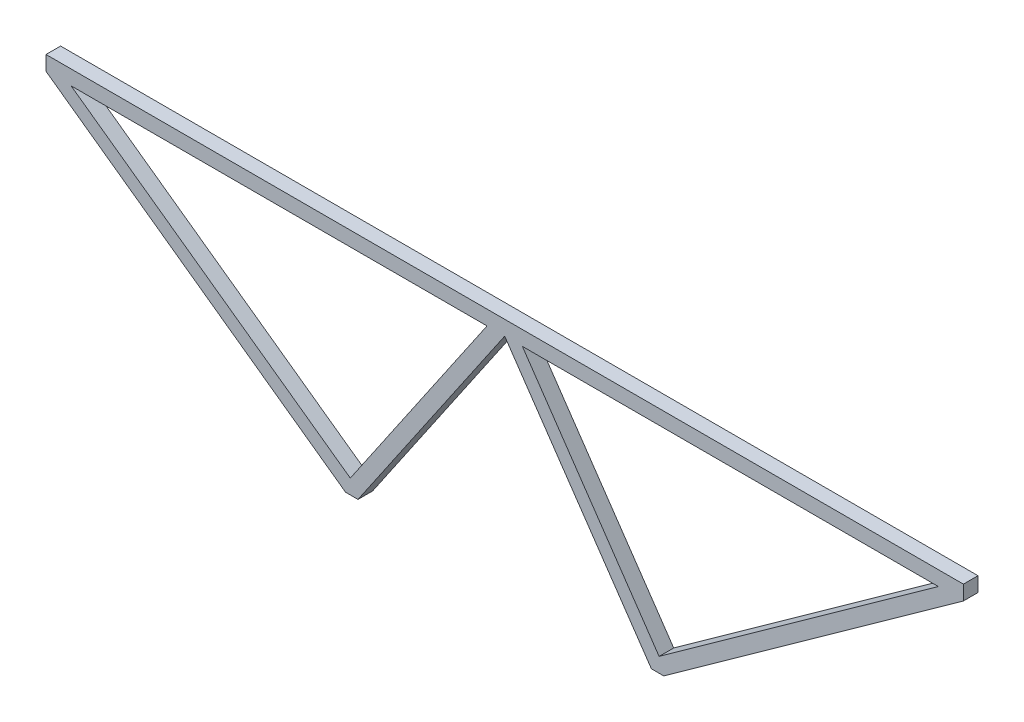
SolidWorks part; units mm, degrees
ref_plane "Front Plane" through (0, 0, 0) normal (0, 0, 1) x (1, 0, 0)
ref_plane "Top Plane" through (0, 0, 0) normal (0, 1, 0) x (1, 0, 0)
ref_plane "Right Plane" through (0, 0, 0) normal (1, 0, 0) x (0, 0, -1)
sketch "Sketch3" plane through (0, 0, 0) normal (0, 0, 1) x (1, 0, 0)
  line L0 (391.8891, -300) -> (408.1109, -300)
  line L2 (0, 0) -> (0, -19.1)
  line L3 (32.7851, -19.1) -> (576.8688, -19.1)
  line L7 (576.8688, -19.1) -> (398.0274, -280.9)
  line L8 (398.0274, -280.9) -> (32.7851, -19.1)
  line L17 (391.8891, -300) -> (0, -19.1)
  line L18 (408.1109, -300) -> (600, -19.1)
  line L19 (0, 0) -> (1200, 0)
  line L21 (600, 186.1009) -> (600, -613.1506) construction
  line L22 (791.8891, -300) -> (600, -19.1)
  line L23 (808.1109, -300) -> (1200, -19.1)
  line L24 (801.9726, -280.9) -> (1167.2149, -19.1)
  line L25 (623.1312, -19.1) -> (801.9726, -280.9)
  line L26 (1167.2149, -19.1) -> (623.1312, -19.1)
  line L27 (1200, 0) -> (1200, -19.1)
  line L28 (808.1109, -300) -> (791.8891, -300)
  point P1 (400, -300)
  point P14 (600, 0)
  dimension "D1" = 600
  dimension "D2" = 300
  dimension "D3" = 400
  dimension "D4" = 19.1
  dimension "D5" = 19.1
  dimension "D6" = 19.1
  dimension "D7" = 19.1
  dimension "D8" = 19.1
  dimension "D9" = 19.1
extrude "Boss-Extrude2" add sketch "Sketch3" along normal blind 19.1
